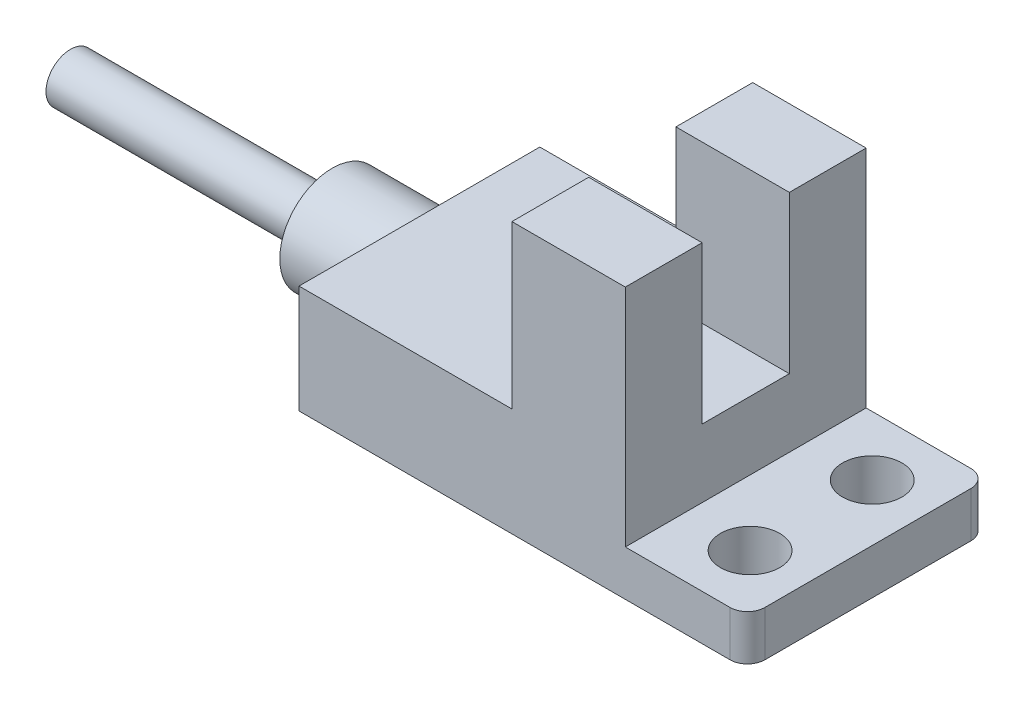
SolidWorks part; units mm, degrees
ref_plane "Plan de face" through (0, 0, 0) normal (0, 0, 1) x (1, 0, 0)
ref_plane "Plan de dessus" through (0, 0, 0) normal (0, 1, 0) x (1, 0, 0)
ref_plane "Plan de droite" through (0, 0, 0) normal (1, 0, 0) x (0, 0, -1)
sketch "Esquisse1" plane through (0, 0, 0) normal (0, 0, 1) x (1, 0, 0)
  line L0 (-15.45, 0) -> (10.25, 0)
  line L1 (10.25, 0) -> (10.25, 2.6)
  line L2 (10.25, 2.6) -> (3.25, 2.6)
  line L3 (3.25, 2.6) -> (3.25, 15.5)
  line L4 (3.25, 15.5) -> (-3.25, 15.5)
  line L5 (-3.25, 15.5) -> (-3.25, 6.2)
  line L6 (-3.25, 6.2) -> (-15.45, 6.2)
  line L7 (-15.45, 6.2) -> (-15.45, 0)
  point P3 (0, 15.5)
  dimension "D1" = 2.6
  dimension "D2" = 6.2
  dimension "D3" = 6.5
  dimension "D4" = 15.5
  dimension "D5" = 25.7
  dimension "D6" = 7
extrude "Boss.-Extru.1" add sketch "Esquisse1" along normal mid plane 13.8
sketch "Esquisse2" plane through (0, 0, 0) normal (1, 0, 0) x (0, 0, -1)
  line L0 (-6.9, 15.5) -> (6.9, 15.5) construction
  line L1 (-2.5, 15.5) -> (2.5, 15.5)
  line L2 (-2.5, 15.5) -> (-2.5, 6.5)
  line L3 (-2.5, 6.5) -> (2.5, 6.5)
  line L4 (2.5, 15.5) -> (2.5, 6.5)
  point P6 (0, 6.5)
  dimension "D1" = 5
  dimension "D2" = 9
extrude "Enlèv. mat.-Extru.1" cut sketch "Esquisse2" against normal through all both and the other way through all
hole_wizard "Dégagement M31" positions "Esquisse3" profile "Esquisse4" hole size "M3" standard "ISO" end condition through all
sketch "Esquisse3" plane through (0, 2.6, 0) normal (0, 1, 0) x (1, 0, 0)
  line L0 (0, 0) -> (1.773, 0) construction
  point P0 (7, 3.5)
  point P7 (7, -3.5)
  dimension "D1" = 7
  dimension "D2" = 7
sketch "Esquisse4" plane through (7, 2.6, -3.5) normal (1, 0, 0) x (0, 0, 1)
  line L0 (0, 0) -> (0, 2.6)
  line L1 (0, 2.6) -> (1.7, 2.6)
  line L2 (1.7, 2.6) -> (1.7, 0)
  line L5 (1.7, 0) -> (0, 0)
  line L11 (0, -6.35) -> (0, 107.95) construction
  dimension "Diamètre du perçage jusqu'au prochain" = 3.4
  dimension "Profondeur du perçage jusqu'au prochain" = 2.6
sketch "Esquisse5" plane through (-15.45, 0, 0) normal (-1, 0, 0) x (0, 0, 1)
  line L0 (0, 6.2) -> (0, 0) construction
  line L1 (6.9, 6.2) -> (-6.9, 6.2) construction
  circle A0 centre (0, 3.1) radius 3
  point P2 (0, 3.1)
  dimension "D1" = 6
extrude "Boss.-Extru.2" add sketch "Esquisse5" along normal blind 5
sketch "Esquisse6" plane through (-20.45, 0, 0) normal (-1, 0, 0) x (0, 0, 1)
  circle A0 centre (0, 3.1) radius 1.4
  dimension "D1" = 2.8
extrude "Boss.-Extru.3" add sketch "Esquisse6" along normal blind 15
fillet "Congé1" radius 1 2 edges at (10.25, 1.3, -6.9) (10.25, 1.3, 6.9)
